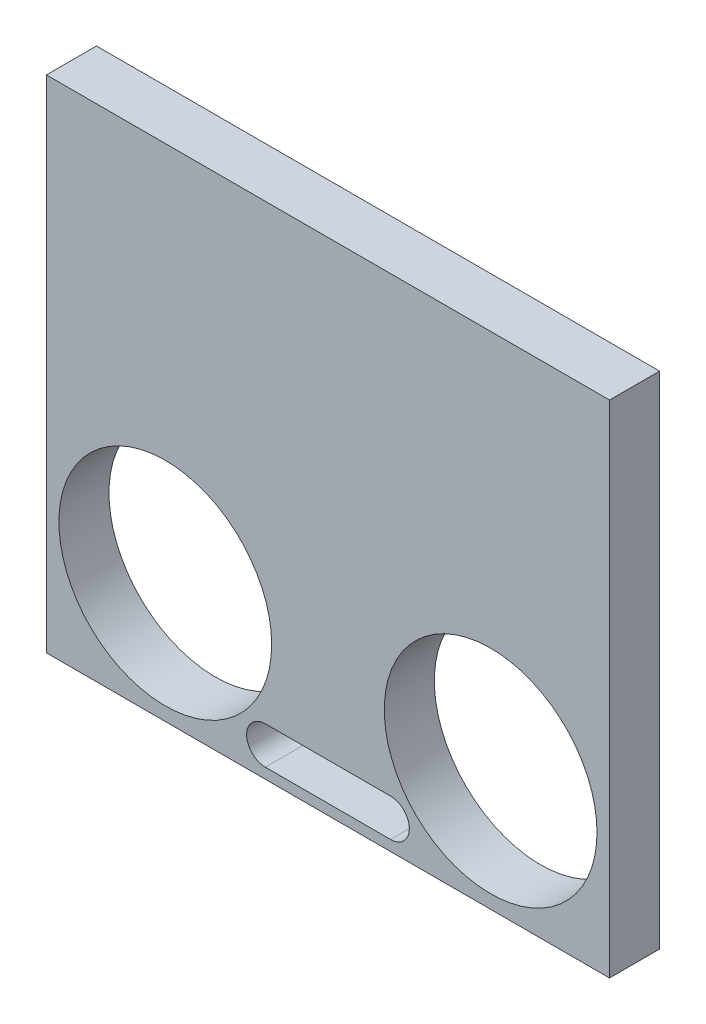
SolidWorks part; units mm, degrees
ref_plane "Plan de face" through (0, 0, 0) normal (0, 0, 1) x (1, 0, 0)
ref_plane "Plan de dessus" through (0, 0, 0) normal (0, 1, 0) x (1, 0, 0)
ref_plane "Plan de droite" through (0, 0, 0) normal (1, 0, 0) x (0, 0, -1)
sketch "Sketch1" plane through (0, 0, 0) normal (0, 0, 1) x (1, 0, 0)
  line L0 (4.0601, -15.6699) -> (14.0601, -15.6699) construction
  line L5 (-13.4399, 21.9913) -> (31.5601, 21.9913)
  line L6 (-13.4399, 21.9913) -> (-13.4399, -18.0087)
  line L7 (-13.4399, -18.0087) -> (31.5601, -18.0087)
  line L8 (31.5601, 21.9913) -> (31.5601, -18.0087)
  line L9 (4.0601, -14.1699) -> (14.0601, -14.1699)
  line L10 (4.0601, -17.1699) -> (14.0601, -17.1699)
  circle A0 centre (22.0601, -8.4306) radius 8.5
  circle A1 centre (-3.9399, -8.4306) radius 8.5
  arc A2 (4.0601, -14.1699) -> (4.0601, -17.1699) centre (4.0601, -15.6699) ccw
  arc A3 (14.0601, -17.1699) -> (14.0601, -14.1699) centre (14.0601, -15.6699) ccw
  point P10 (9.0601, -15.6699)
  dimension "D3" = 17
  dimension "D4" = 17
  dimension "D1" = 40
  dimension "D2" = 45
  dimension "D5" = 10
  dimension "D6" = 3
  dimension "D7" = 26
  dimension "D8" = 22.5
  dimension "D9" = 22.5
  dimension "D10" = 9.5
  dimension "D11" = 9.5
  dimension "D12" = 26
extrude "Boss-Extrude1" add sketch "Sketch1" along normal blind 4
